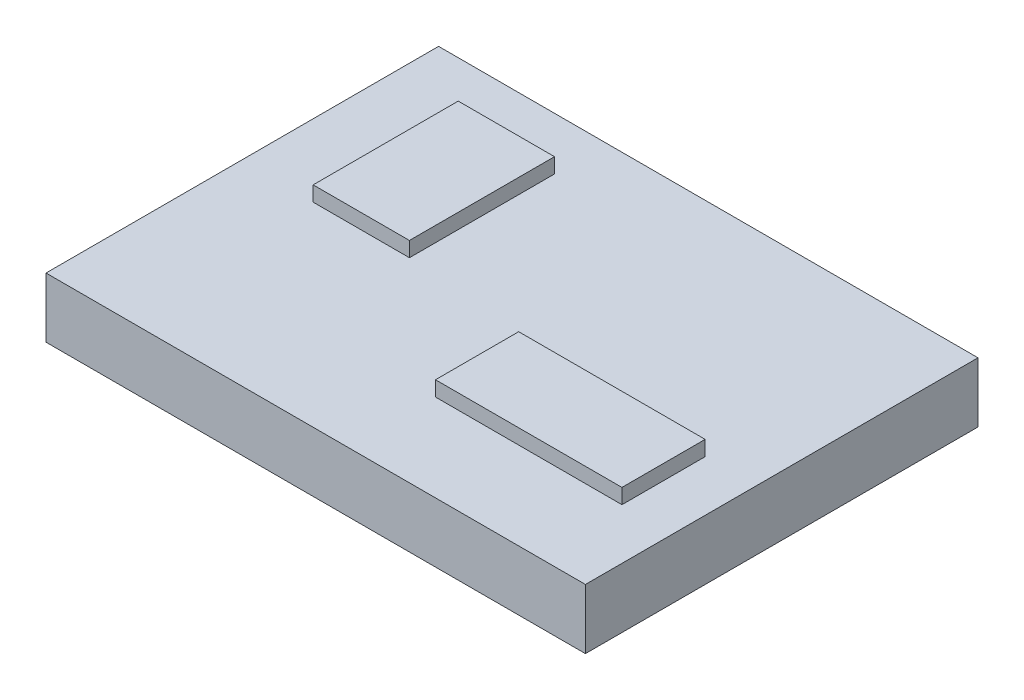
SolidWorks part; units mm, degrees
ref_plane "Front" through (0, 0, 0) normal (0, 0, 1) x (1, 0, 0)
ref_plane "Top" through (0, 0, 0) normal (0, 1, 0) x (1, 0, 0)
ref_plane "Right" through (0, 0, 0) normal (1, 0, 0) x (0, 0, -1)
sketch "Sketch1" plane through (0, 0, 0) normal (0, 1, 0) x (1, 0, 0)
  line L1 (0, 0) -> (18, 0)
  line L2 (0, 0) -> (0, 13.1)
  line L3 (0, 13.1) -> (18, 13.1)
  line L4 (18, 0) -> (18, 13.1)
  dimension "D1" = 18
  dimension "D2" = 13.1
extrude "Boss-Extrude1" add sketch "Sketch1" along normal blind 2
sketch "Sketch2" plane through (0, 2, 0) normal (0, 1, 0) x (1, 0, 0)
  line L1 (2.4098, 11.3459) -> (5.6225, 11.3459)
  line L2 (2.4098, 11.3459) -> (2.4098, 6.5048)
  line L3 (2.4098, 6.5048) -> (5.6225, 6.5048)
  line L4 (5.6225, 11.3459) -> (5.6225, 6.5048)
  line L5 (10.0829, 5.6903) -> (16.305, 5.6903)
  line L6 (10.0829, 5.6903) -> (10.0829, 2.9141)
  line L7 (10.0829, 2.9141) -> (16.305, 2.9141)
  line L8 (16.305, 5.6903) -> (16.305, 2.9141)
extrude "Boss-Extrude2" add sketch "Sketch2" along normal blind 0.5
